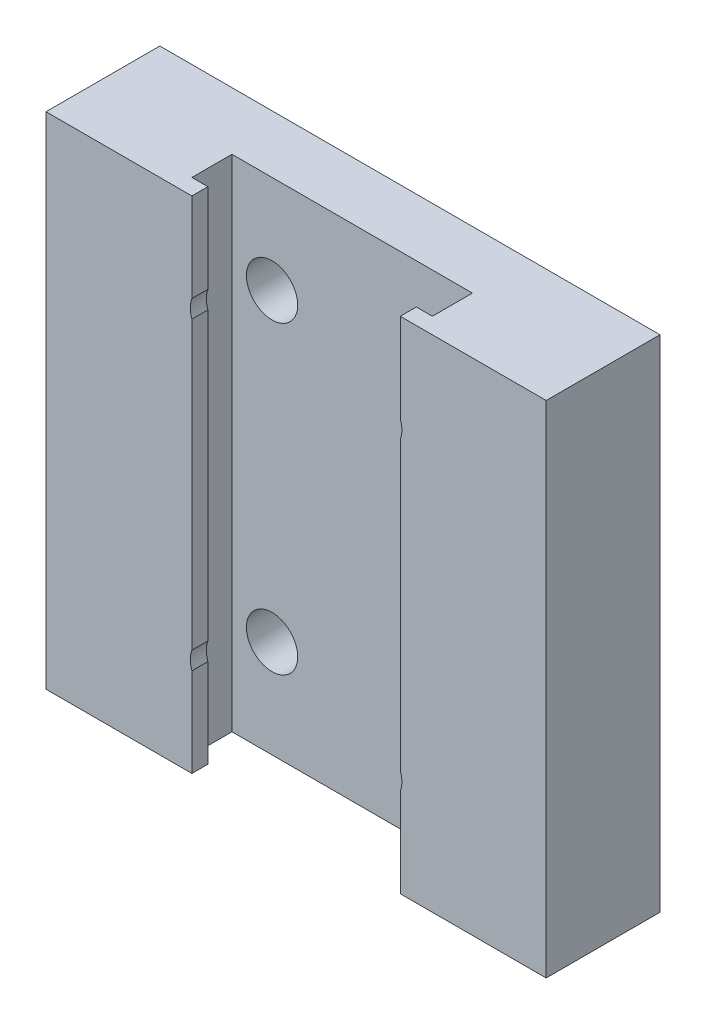
SolidWorks part; units mm, degrees
ref_plane "前视基准面" through (0, 0, 0) normal (0, 0, 1) x (1, 0, 0)
ref_plane "上视基准面" through (0, 0, 0) normal (0, 1, 0) x (1, 0, 0)
ref_plane "右视基准面" through (0, 0, 0) normal (1, 0, 0) x (0, 0, -1)
sketch "草图1" plane through (0, 0, 0) normal (0, 1, 0) x (1, 0, 0)
  line L0 (-7.5, -0.2751) -> (-6.5, -0.2751)
  line L1 (-6.5, -0.2751) -> (-6.5, -1.2751)
  line L2 (-6.5, -1.2751) -> (-15.6, -1.2751)
  line L3 (-15.6, -1.2751) -> (-15.6, 5.8249)
  line L4 (-15.6, 5.8249) -> (15.6, 5.8249)
  line L6 (7.5, 2.2249) -> (-7.5, 2.2249)
  line L7 (-7.5, 2.2249) -> (-7.5, -0.2751)
  line L8 (0, 5.8249) -> (0, -2.3974) construction
  line L9 (7.5, 2.2249) -> (7.5, -0.2751)
  line L10 (15.6, -1.2751) -> (15.6, 5.8249)
  line L11 (6.5, -1.2751) -> (15.6, -1.2751)
  line L12 (6.5, -0.2751) -> (6.5, -1.2751)
  line L13 (7.5, -0.2751) -> (6.5, -0.2751)
  point P12 (0, 2.2249)
  dimension "D1" = 7.1
  dimension "D2" = 31.2
  dimension "D3" = 1
  dimension "D4" = 1
  dimension "D5" = 2.5
  dimension "D6" = 7.5
extrude "凸台-拉伸1" add sketch "草图1" along normal blind 31.2
sketch "草图2" plane through (0, 0, -5.8249) normal (0, 0, -1) x (-1, 0, 0)
  line L0 (0, 31.2) -> (0, -6.1748) construction
  line L1 (-15.6, 31.2) -> (15.6, 31.2) construction
  line L2 (-15.6, 15.6) -> (19.4723, 15.6) construction
  line L3 (-15.6, 31.2) -> (-15.6, 0) construction
  circle A0 centre (-5, 25.1) radius 1.6
  circle A1 centre (5, 25.1) radius 1.6
  circle A2 centre (5, 6.1) radius 1.6
  circle A3 centre (-5, 6.1) radius 1.6
  dimension "D1" = 3.2
  dimension "D2" = 10
  dimension "D3" = 19
extrude "切除-拉伸1" cut sketch "草图2" against normal blind 10
